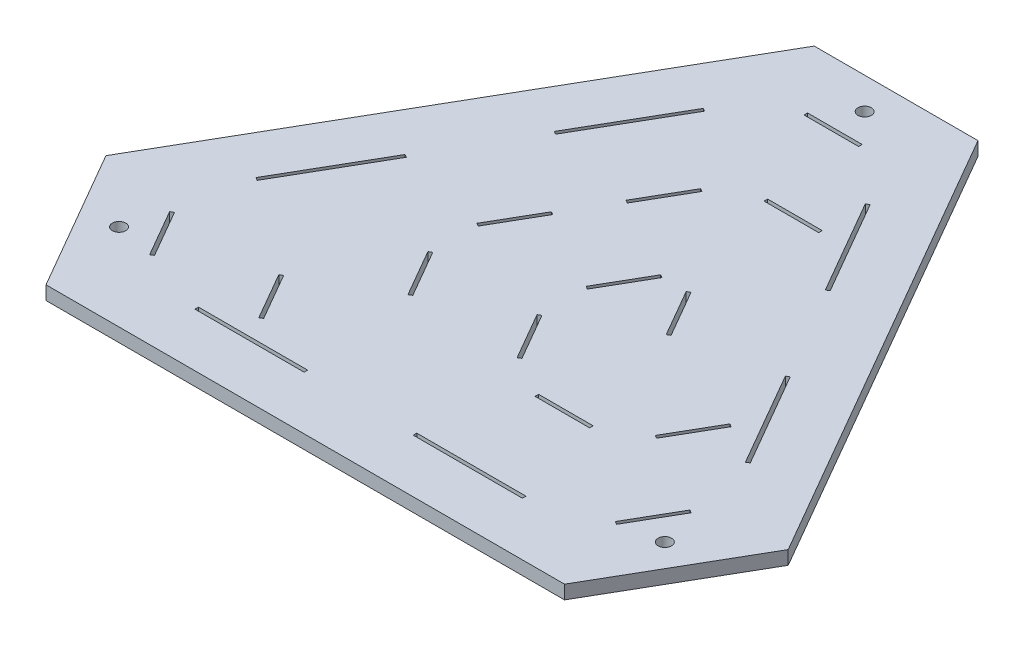
SolidWorks part; units mm, degrees
ref_plane "Front Plane" through (0, 0, 0) normal (0, 0, 1) x (1, 0, 0)
ref_plane "Top Plane" through (0, 0, 0) normal (0, 1, 0) x (1, 0, 0)
ref_plane "Right Plane" through (0, 0, 0) normal (1, 0, 0) x (0, 0, -1)
sketch "Sketch1" plane through (0, 0, 0) normal (0, 1, 0) x (1, 0, 0)
  line L0 (-60, 254.0341) -> (60, 254.0341)
  line L1 (-60, 254.0341) -> (-250, -75.0555)
  line L2 (-250, -75.0555) -> (-190, -178.9786)
  line L3 (-190, -178.9786) -> (190, -178.9786)
  line L4 (190, -178.9786) -> (250, -75.0555)
  line L5 (250, -75.0555) -> (60, 254.0341)
  line L6 (180, -103.923) -> (-120, 69.282) construction
  line L7 (-180, -103.923) -> (0, 0) construction
  line L8 (-220, -127.0171) -> (-180, -103.923) construction
  line L9 (180, -103.923) -> (220, -127.0171) construction
  line L10 (0, 254.0341) -> (0, 207.8461) construction
  line L11 (0, 138.5641) -> (-40, 69.282) construction
  line L12 (-120, -69.282) -> (-80, -138.5641) construction
  line L13 (-80, 0) -> (-40, -69.282) construction
  line L14 (40, -69.282) -> (120, -69.282) construction
  line L15 (40, 207.8461) -> (-40, 207.8461) construction
  line L16 (-40, 207.8461) -> (-200, -69.282) construction
  line L17 (-200, -69.282) -> (-160, -138.5641) construction
  line L18 (-160, -138.5641) -> (160, -138.5641) construction
  line L19 (160, -138.5641) -> (200, -69.282) construction
  line L20 (200, -69.282) -> (40, 207.8461) construction
  line L21 (40, -69.282) -> (0, 0) construction
  line L22 (0, 0) -> (40, 69.282) construction
  line L23 (40, 69.282) -> (80, 0)
  line L24 (0, 138.5641) -> (80, 138.5641) construction
  line L25 (120, -69.282) -> (160, 0) construction
  line L26 (-40, 69.282) -> (-80, 0) construction
  line L27 (-191.1258, -87.2525) -> (-188.8742, -85.9525)
  line L28 (-20, 209.1461) -> (20, 209.1461)
  line L29 (-20, 209.1461) -> (-20, 206.5461)
  line L30 (-220, -127.0171) -> (0, 0) construction
  line L31 (220, -127.0171) -> (-155, 89.4893) construction
  line L32 (-20, 206.5461) -> (20, 206.5461)
  line L33 (20, 209.1461) -> (20, 206.5461)
  line L34 (-20, 209.1461) -> (20, 206.5461) construction
  line L35 (-20, 206.5461) -> (20, 209.1461) construction
  line L36 (-191.1258, -87.2525) -> (-171.1258, -121.8936)
  line L37 (-188.8742, -85.9525) -> (-168.8742, -120.5936)
  line L38 (-171.1258, -121.8936) -> (-168.8742, -120.5936)
  line L39 (-191.1258, -87.2525) -> (-168.8742, -120.5936) construction
  line L40 (-188.8742, -85.9525) -> (-171.1258, -121.8936) construction
  line L41 (188.8742, -85.9525) -> (191.1258, -87.2525)
  line L42 (188.8742, -85.9525) -> (168.8742, -120.5936)
  line L43 (191.1258, -87.2525) -> (171.1258, -121.8936)
  line L44 (168.8742, -120.5936) -> (171.1258, -121.8936)
  line L45 (188.8742, -85.9525) -> (171.1258, -121.8936) construction
  line L46 (191.1258, -87.2525) -> (168.8742, -120.5936) construction
  line L47 (148.8742, -16.6705) -> (151.1258, -17.9705)
  line L48 (148.8742, -16.6705) -> (128.8742, -51.3115)
  line L49 (151.1258, -17.9705) -> (131.1258, -52.6115)
  line L50 (128.8742, -51.3115) -> (131.1258, -52.6115)
  line L51 (148.8742, -16.6705) -> (131.1258, -52.6115) construction
  line L52 (151.1258, -17.9705) -> (128.8742, -51.3115) construction
  line L53 (-51.1258, 52.6115) -> (-48.8742, 51.3115)
  line L54 (-51.1258, 52.6115) -> (-71.1258, 17.9705)
  line L55 (-48.8742, 51.3115) -> (-68.8742, 16.6705)
  line L56 (-71.1258, 17.9705) -> (-68.8742, 16.6705)
  line L57 (-51.1258, 52.6115) -> (-68.8742, 16.6705) construction
  line L58 (-48.8742, 51.3115) -> (-71.1258, 17.9705) construction
  line L59 (-11.1258, 121.8936) -> (-8.8742, 120.5936)
  line L60 (-11.1258, 121.8936) -> (-31.1258, 87.2525)
  line L61 (-8.8742, 120.5936) -> (-28.8742, 85.9525)
  line L62 (-31.1258, 87.2525) -> (-28.8742, 85.9525)
  line L63 (-11.1258, 121.8936) -> (-28.8742, 85.9525) construction
  line L64 (-8.8742, 120.5936) -> (-31.1258, 87.2525) construction
  line L65 (28.8742, 52.6115) -> (31.1258, 51.3115)
  line L66 (28.8742, 52.6115) -> (8.8742, 17.9705)
  line L67 (31.1258, 51.3115) -> (11.1258, 16.6705)
  line L68 (8.8742, 17.9705) -> (11.1258, 16.6705)
  line L69 (28.8742, 52.6115) -> (11.1258, 16.6705) construction
  line L70 (31.1258, 51.3115) -> (8.8742, 17.9705) construction
  line L71 (-61.1258, 173.8551) -> (-58.8742, 172.5551)
  line L72 (-61.1258, 173.8551) -> (-101.1258, 104.573)
  line L73 (-58.8742, 172.5551) -> (-98.8742, 103.273)
  line L74 (-101.1258, 104.573) -> (-98.8742, 103.273)
  line L75 (-61.1258, 173.8551) -> (-98.8742, 103.273) construction
  line L76 (-58.8742, 172.5551) -> (-101.1258, 104.573) construction
  line L77 (-141.1258, 35.291) -> (-138.8742, 33.991)
  line L78 (-141.1258, 35.291) -> (-181.1258, -33.991)
  line L79 (-138.8742, 33.991) -> (-178.8742, -35.291)
  line L80 (-181.1258, -33.991) -> (-178.8742, -35.291)
  line L81 (-141.1258, 35.291) -> (-178.8742, -35.291) construction
  line L82 (-138.8742, 33.991) -> (-181.1258, -33.991) construction
  line L83 (20, 139.8641) -> (60, 139.8641)
  line L84 (20, 139.8641) -> (20, 137.2641)
  line L85 (20, 137.2641) -> (60, 137.2641)
  line L86 (60, 139.8641) -> (60, 137.2641)
  line L87 (20, 139.8641) -> (60, 137.2641) construction
  line L88 (20, 137.2641) -> (60, 139.8641) construction
  line L89 (60, -67.982) -> (100, -67.982)
  line L90 (60, -67.982) -> (60, -70.582)
  line L91 (60, -70.582) -> (100, -70.582)
  line L92 (100, -67.982) -> (100, -70.582)
  line L93 (60, -67.982) -> (100, -70.582) construction
  line L94 (60, -70.582) -> (100, -67.982) construction
  line L95 (-120, -137.2641) -> (-40, -137.2641)
  line L96 (-120, -137.2641) -> (-120, -139.8641)
  line L97 (-120, -139.8641) -> (-40, -139.8641)
  line L98 (-40, -137.2641) -> (-40, -139.8641)
  line L99 (-120, -137.2641) -> (-40, -139.8641) construction
  line L100 (-120, -139.8641) -> (-40, -137.2641) construction
  line L101 (40, -137.2641) -> (120, -137.2641)
  line L102 (40, -137.2641) -> (40, -139.8641)
  line L103 (40, -139.8641) -> (120, -139.8641)
  line L104 (120, -137.2641) -> (120, -139.8641)
  line L105 (40, -137.2641) -> (120, -139.8641) construction
  line L106 (40, -139.8641) -> (120, -137.2641) construction
  line L107 (-111.1258, -87.2525) -> (-108.8742, -85.9525)
  line L108 (-111.1258, -87.2525) -> (-91.1258, -121.8936)
  line L109 (-108.8742, -85.9525) -> (-88.8742, -120.5936)
  line L110 (-91.1258, -121.8936) -> (-88.8742, -120.5936)
  line L111 (-111.1258, -87.2525) -> (-88.8742, -120.5936) construction
  line L112 (-108.8742, -85.9525) -> (-91.1258, -121.8936) construction
  line L113 (-71.1258, -17.9705) -> (-68.8742, -16.6705)
  line L114 (-71.1258, -17.9705) -> (-51.1258, -52.6115)
  line L115 (-68.8742, -16.6705) -> (-48.8742, -51.3115)
  line L116 (-51.1258, -52.6115) -> (-48.8742, -51.3115)
  line L117 (-71.1258, -17.9705) -> (-48.8742, -51.3115) construction
  line L118 (-68.8742, -16.6705) -> (-51.1258, -52.6115) construction
  line L119 (8.8742, -17.9705) -> (11.1258, -16.6705)
  line L120 (8.8742, -17.9705) -> (28.8742, -52.6115)
  line L121 (11.1258, -16.6705) -> (31.1258, -51.3115)
  line L122 (28.8742, -52.6115) -> (31.1258, -51.3115)
  line L123 (8.8742, -17.9705) -> (31.1258, -51.3115) construction
  line L124 (11.1258, -16.6705) -> (28.8742, -52.6115) construction
  line L125 (48.8742, 51.3115) -> (51.1258, 52.6115)
  line L126 (48.8742, 51.3115) -> (68.8742, 16.6705)
  line L127 (51.1258, 52.6115) -> (71.1258, 17.9705)
  line L128 (68.8742, 16.6705) -> (71.1258, 17.9705)
  line L129 (48.8742, 51.3115) -> (71.1258, 17.9705) construction
  line L130 (51.1258, 52.6115) -> (68.8742, 16.6705) construction
  line L131 (58.8636, 172.5734) -> (61.1153, 173.8734)
  line L132 (58.8636, 172.5734) -> (98.8636, 103.2913)
  line L133 (61.1153, 173.8734) -> (101.1153, 104.5913)
  line L134 (98.8636, 103.2913) -> (101.1153, 104.5913)
  line L135 (58.8636, 172.5734) -> (101.1153, 104.5913) construction
  line L136 (61.1153, 173.8734) -> (98.8636, 103.2913) construction
  line L137 (138.8742, 33.991) -> (141.1258, 35.291)
  line L138 (138.8742, 33.991) -> (178.8742, -35.291)
  line L139 (141.1258, 35.291) -> (181.1258, -33.991)
  line L140 (178.8742, -35.291) -> (181.1258, -33.991)
  line L141 (138.8742, 33.991) -> (181.1258, -33.991) construction
  line L142 (141.1258, 35.291) -> (178.8742, -35.291) construction
  circle A0 centre (-200, -115.4701) radius 4.9022
  circle A1 centre (200, -115.4701) radius 4.9022
  circle A2 centre (0, 230.9401) radius 4.9022
  point P12 (120, 69.282)
  point P26 (0, 207.8461)
  point P36 (155, 89.4893)
  point P60 (140, -34.641)
  point P61 (140, -34.641)
  point P67 (-60, 34.641)
  point P68 (-60, 34.641)
  point P73 (-20, 103.923)
  point P74 (-20, 103.923)
  point P79 (20, 34.641)
  point P80 (20, 34.641)
  point P85 (-80, 138.5641)
  point P90 (-160, 0)
  point P96 (40, 138.5641)
  point P97 (40, 138.5641)
  point P102 (80, -69.282)
  point P103 (80, -69.282)
  point P108 (-80, -138.5641)
  point P113 (80, -138.5641)
  point P118 (-100, -103.923)
  point P119 (-100, -103.923)
  point P124 (-60, -34.641)
  point P125 (-60, -34.641)
  point P130 (20, -34.641)
  point P131 (20, -34.641)
  point P136 (60, 34.641)
  point P137 (60, 34.641)
  point P142 (79.9894, 138.5824)
  point P147 (160, 0)
  line B0 (669.7258, 410.0613) -> (369.7258, -109.5539) construction
  line B1 (519.7258, 392.7408) -> (819.7258, -126.8744) construction
  line B2 (699.7258, 392.7408) -> (399.7258, -126.8744) construction
  line B3 (729.7258, 375.4203) -> (429.7258, -144.1949) construction
  line B4 (759.7258, 358.0998) -> (459.7258, -161.5155) construction
  line B5 (789.7258, 340.7793) -> (489.7258, -178.836) construction
  line B6 (819.7258, 323.4588) -> (519.7258, -196.1565) construction
  line B7 (849.7258, 306.1383) -> (549.7258, -213.477) construction
  line B8 (879.7258, 288.8178) -> (579.7258, -230.7975) construction
  line B9 (909.7258, 271.4972) -> (609.7258, -248.118) construction
  line B10 (939.7258, 254.1767) -> (639.7258, -265.4385) construction
  line B11 (549.7258, 410.0613) -> (849.7258, -109.5539) construction
  line B12 (489.7258, 375.4203) -> (789.7258, -144.1949) construction
  line B13 (459.7258, 358.0998) -> (759.7258, -161.5155) construction
  line B14 (429.7258, 340.7793) -> (729.7258, -178.836) construction
  line B15 (399.7258, 323.4588) -> (699.7258, -196.1565) construction
  line B16 (369.7258, 306.1383) -> (669.7258, -213.477) construction
  line B17 (339.7258, 288.8178) -> (639.7258, -230.7975) construction
  line B18 (309.7258, 271.4972) -> (609.7258, -248.118) construction
  line B19 (279.7258, 254.1767) -> (579.7258, -265.4385) construction
  line B20 (309.7258, -5.6309) -> (909.7258, -5.6309) construction
  line B21 (309.7258, 29.0101) -> (909.7258, 29.0101) construction
  line B22 (309.7258, 63.6512) -> (909.7258, 63.6512) construction
  line B23 (309.7258, 98.2922) -> (909.7258, 98.2922) construction
  line B24 (309.7258, 132.9332) -> (909.7258, 132.9332) construction
  line B25 (309.7258, 167.5742) -> (909.7258, 167.5742) construction
  line B26 (309.7258, 202.2152) -> (909.7258, 202.2152) construction
  line B27 (309.7258, 236.8562) -> (909.7258, 236.8562) construction
  line B28 (309.7258, 271.4972) -> (909.7258, 271.4972) construction
  line B29 (309.7258, 306.1383) -> (909.7258, 306.1383) construction
  dimension "D10" = 9.8044
  dimension "D11" = 9.8044
  dimension "D12" = 9.8044
  dimension "D1" = 120
  dimension "D2" = 120
  dimension "D3" = 380
  dimension "D4" = 120
  dimension "D5" = 80
  dimension "D6" = 120
  dimension "D7" = 120
  dimension "D8" = 320
  dimension "D9" = 120
  dimension "D13" = 2.6
  dimension "D15" = 90
  dimension "D16" = 2.6
  dimension "D18" = 2.6
  dimension "D14" = 40
  dimension "D17" = 40
  dimension "D19" = 40
  dimension "D20" = 40
  dimension "D21" = 2.6
  dimension "D22" = 2.6
  dimension "D23" = 40
  dimension "D24" = 80
  dimension "D25" = 2.6
  dimension "D26" = 40
  dimension "D27" = 80
  dimension "D28" = 40
  dimension "D29" = 2.6
  dimension "D30" = 40
  dimension "D31" = 2.6
  dimension "D32" = 40
  dimension "D33" = 2.6
  dimension "D34" = 80
  dimension "D35" = 2.6
  dimension "D36" = 40
  dimension "D37" = 2.6
  dimension "D38" = 40
  dimension "D39" = 80
  dimension "D40" = 40
  dimension "D41" = 2.6
  dimension "D42" = 40
  dimension "D43" = 2.6
  dimension "D44" = 2.6
  dimension "D45" = 40
  dimension "D46" = 2.6
  dimension "D47" = 40
  dimension "D48" = 2.6
  dimension "D49" = 40
  dimension "D50" = 2.6
  dimension "D51" = 40
  dimension "D52" = 2.6
  dimension "D53" = 80
  dimension "D54" = 2.6
  dimension "D55" = 80
  dimension "D56" = 40
  dimension "D57" = 40
sketch_block_instance "Block1-1"
sketch_block "Block1" parameters "D1"=600, "D2"=600, "D3"=600
extrude "Boss-Extrude4" add sketch "Sketch1" along normal blind 10
